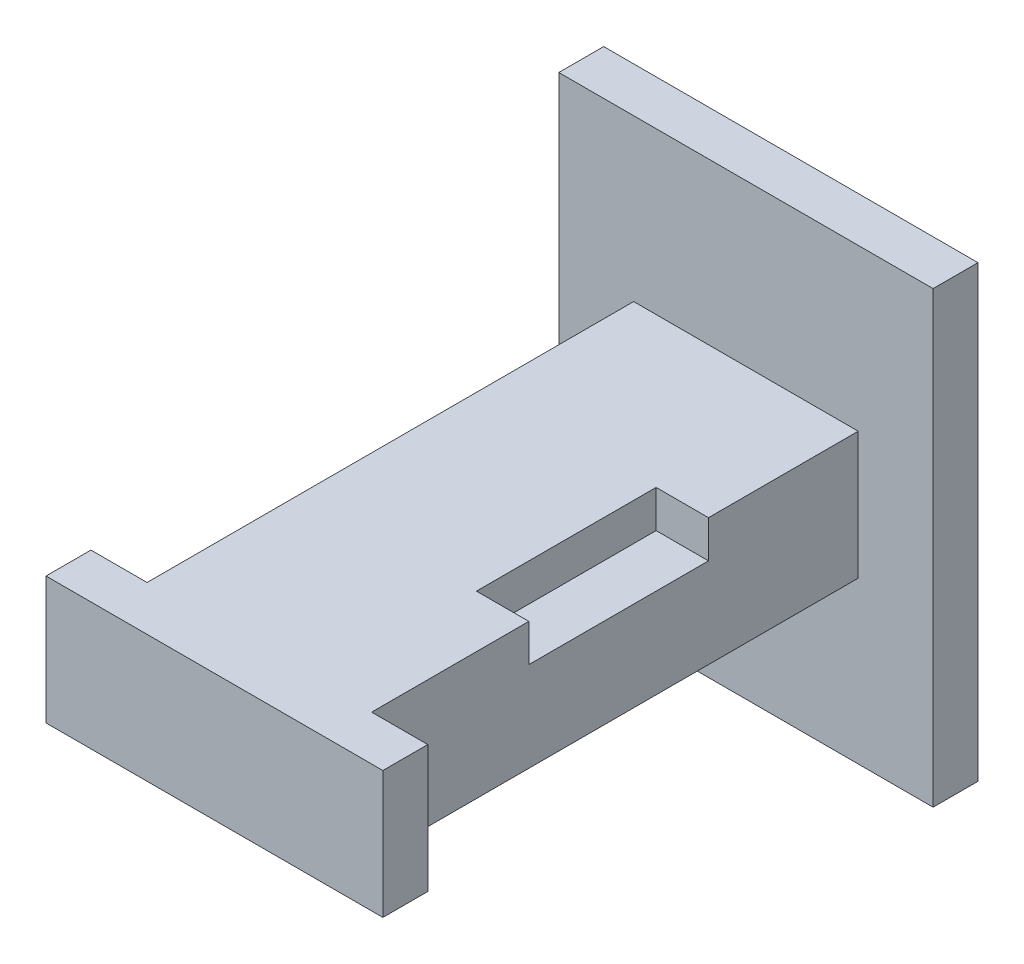
SolidWorks part; units mm, degrees
ref_plane "Спереди" through (0, 0, 0) normal (0, 0, 1) x (1, 0, 0)
ref_plane "Сверху" through (0, 0, 0) normal (0, 1, 0) x (1, 0, 0)
ref_plane "Справа" through (0, 0, 0) normal (1, 0, 0) x (0, 0, -1)
sketch "Эскиз1" plane through (0, 0, 0) normal (0, 0, 1) x (1, 0, 0)
  line L1 (-25, -30) -> (25, -30)
  line L2 (-25, -30) -> (-25, 30)
  line L3 (-25, 30) -> (25, 30)
  line L4 (25, -30) -> (25, 30)
  line L5 (-25, -30) -> (25, 30) construction
  line L6 (-25, 30) -> (25, -30) construction
  point P0 (0, 0)
  dimension "D1" = 50
  dimension "D2" = 60
extrude "Бобышка-Вытянуть1" add sketch "Эскиз1" along normal blind 6
sketch "Эскиз2" plane through (0, 0, 6) normal (0, 0, 1) x (1, 0, 0)
  line L1 (-15, -8.5) -> (15, -8.5)
  line L2 (-15, -8.5) -> (-15, 8.5)
  line L3 (-15, 8.5) -> (15, 8.5)
  line L4 (15, -8.5) -> (15, 8.5)
  line L5 (-15, -8.5) -> (15, 8.5) construction
  line L6 (-15, 8.5) -> (15, -8.5) construction
  point P0 (0, 0)
  dimension "D1" = 30
  dimension "D2" = 17
extrude "Бобышка-Вытянуть2" add sketch "Эскиз2" along normal blind 65
sketch "Эскиз3" plane through (0, 0, 71) normal (0, 0, 1) x (1, 0, 0)
  line L1 (-22.5, -15) -> (22.5, -15)
  line L2 (-22.5, -15) -> (-22.5, 15)
  line L3 (-22.5, 15) -> (22.5, 15)
  line L4 (22.5, -15) -> (22.5, 15)
  line L5 (-22.5, -15) -> (22.5, 15) construction
  line L6 (-22.5, 15) -> (22.5, -15) construction
  point P0 (0, 0)
  dimension "D1" = 45
  dimension "D2" = 30
extrude "Бобышка-Вытянуть3" add sketch "Эскиз3" along normal blind 6
sketch "Эскиз4" plane through (-15, 0, 0) normal (-1, 0, 0) x (0, 0, 1)
  line L0 (71, -8.5) -> (6, -8.5) construction
  line L1 (33, -8.5) -> (51, -8.5)
  line L2 (33, -8.5) -> (33, 4.5)
  line L3 (33, 4.5) -> (51, 4.5)
  line L4 (51, -8.5) -> (51, 4.5)
  line L5 (71, 8.5) -> (6, 8.5) construction
  line L6 (6, 30) -> (6, -30) construction
  dimension "D1" = 4
  dimension "D2" = 27
  dimension "D3" = 18
extrude "Вырез-Вытянуть1" cut sketch "Эскиз4" against normal blind 10
sketch "Эскиз5" plane through (15, 0, 0) normal (1, 0, 0) x (0, 0, -1)
  line L0 (-71, 8.5) -> (-6, 8.5) construction
  line L1 (-50, 8.5) -> (-26, 8.5)
  line L2 (-50, 8.5) -> (-50, 3.5)
  line L3 (-50, 3.5) -> (-26, 3.5)
  line L4 (-26, 8.5) -> (-26, 3.5)
  line L5 (-6, -8.5) -> (-6, 8.5) construction
  dimension "D1" = 20
  dimension "D2" = 24
  dimension "D3" = 5
extrude "Вырез-Вытянуть2" cut sketch "Эскиз5" against normal blind 7
sketch "Эскиз6" plane through (0, 15, 0) normal (0, 1, 0) x (1, 0, 0)
  line L4 (22.5, -71) -> (-22.5, -71)
  line L5 (-22.5, -71) -> (-22.5, -77)
  line L6 (-22.5, -77) -> (22.5, -77)
  line L7 (22.5, -77) -> (22.5, -71)
  line L8 (22.5, -71) -> (-22.5, -71)
  line L9 (-22.5, -71) -> (-22.5, -77)
  line L10 (-22.5, -77) -> (22.5, -77)
  line L11 (22.5, -77) -> (22.5, -71)
  dimension "D1" = 0
extrude "Вырез-Вытянуть3" cut sketch "Эскиз6" against normal up to surface (6.5 mm away) up to face at (5.75, 8.5, 38.25)
sketch "Эскиз7" plane through (0, -15, 0) normal (0, -1, 0) x (1, 0, 0)
  line L4 (-22.5, 71) -> (22.5, 71)
  line L5 (22.5, 71) -> (22.5, 77)
  line L6 (22.5, 77) -> (-22.5, 77)
  line L7 (-22.5, 77) -> (-22.5, 71)
  line L8 (-22.5, 71) -> (22.5, 71)
  line L9 (22.5, 71) -> (22.5, 77)
  line L10 (22.5, 77) -> (-22.5, 77)
  line L11 (-22.5, 77) -> (-22.5, 71)
  dimension "D1" = 0
extrude "Вырез-Вытянуть4" cut sketch "Эскиз7" against normal up to surface (6.5 mm away) up to face at (-5, -8.5, 40.25)
